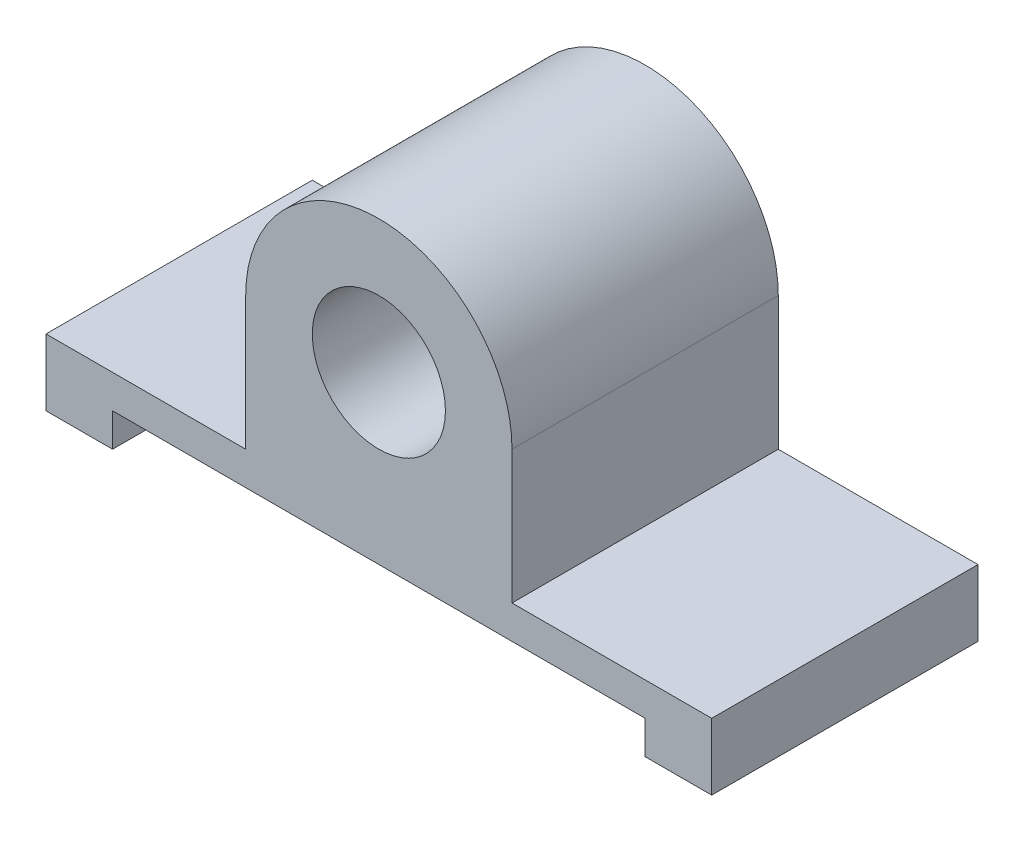
SolidWorks part; units mm, degrees
ref_plane "Front Plane" through (0, 0, 0) normal (0, 0, 1) x (1, 0, 0)
ref_plane "Top Plane" through (0, 0, 0) normal (0, 1, 0) x (1, 0, 0)
ref_plane "Right Plane" through (0, 0, 0) normal (1, 0, 0) x (0, 0, -1)
sketch "Sketch1" plane through (0, 0, 0) normal (0, 0, 1) x (1, 0, 0)
  line L0 (0, 0) -> (0, -33308.1332) construction
  line L1 (0, 0) -> (33308.1332, 0) construction
  line L2 (50, 0) -> (50, 10)
  line L3 (50, 10) -> (20, 10)
  line L4 (-20, 10) -> (-50, 10)
  line L5 (-50, 10) -> (-50, 0)
  line L6 (-50, 0) -> (-40, 0)
  line L7 (-40, 0) -> (-40, 5)
  line L8 (-40, 5) -> (40, 5)
  line L9 (40, 5) -> (40, 0)
  line L10 (40, 0) -> (50, 0)
  line L11 (-20, 10) -> (-20, 30)
  line L12 (20, 30) -> (20, 10)
  arc A1 (-20, 30) -> (20, 30) centre (0, 30) cw
  circle A2 centre (0, 30) radius 10
  dimension "D7" = 20
  dimension "D8" = 20
  dimension "D1" = 80
  dimension "D2" = 10
  dimension "D3" = 10
  dimension "D4" = 10
  dimension "D5" = 20
  dimension "D6" = 5
extrude "Boss-Extrude1" add sketch "Sketch1" along normal mid plane 40
